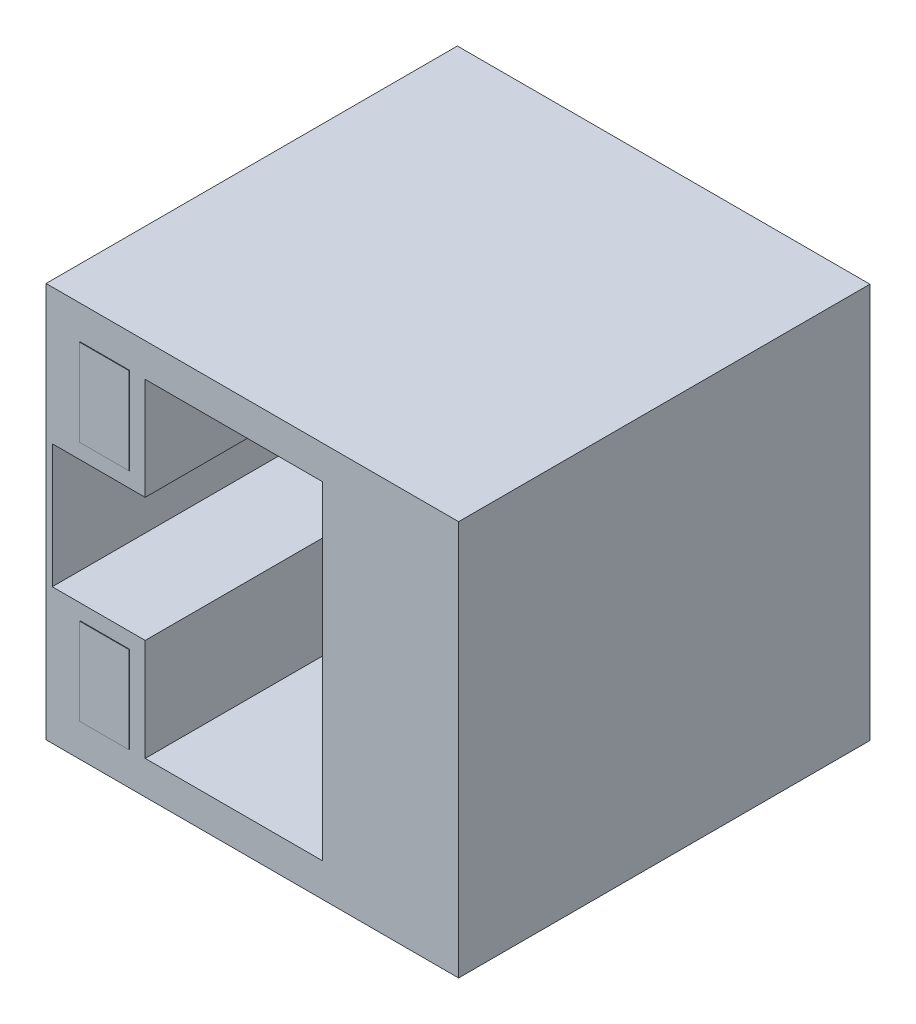
SolidWorks part; units mm, degrees
ref_plane "Front Plane" through (0, 0, 0) normal (0, 0, 1) x (1, 0, 0)
ref_plane "Top Plane" through (0, 0, 0) normal (0, 1, 0) x (1, 0, 0)
ref_plane "Right Plane" through (0, 0, 0) normal (1, 0, 0) x (0, 0, -1)
ref_plane "Plane1" through (0, 8.1026, 0) normal (0, 1, 0) x (-1, 0, 0)
sketch "Sketch1" plane through (0, 8.1026, 0) normal (0, 1, 0) x (-1, 0, 0)
  line L0 (-8.4582, -8.4328) -> (8.4582, -8.4328)
  line L1 (8.4582, -8.4328) -> (8.4582, 8.4328)
  line L2 (8.4582, 8.4328) -> (-8.4582, 8.4328)
  line L3 (-8.4582, 8.4328) -> (-8.4582, -8.4328)
extrude "Boss-Extrude1" add sketch "Sketch1" against normal blind 16.2052
ref_plane "Plane2" through (0, 0, 8.4582) normal (0, 0, 1) x (1, 0, 0)
sketch "Sketch2" plane through (0, 0, 8.4582) normal (0, 0, 1) x (1, 0, 0)
  line L0 (-7.0612, -3.175) -> (-7.0612, -6.731)
  line L1 (-7.0612, -6.731) -> (-5.0292, -6.731)
  line L2 (-5.0292, -6.731) -> (-5.0292, -3.175)
  line L3 (-5.0292, -3.175) -> (-7.0612, -3.175)
  line L4 (-7.0612, 6.731) -> (-7.0612, 3.175)
  line L5 (-7.0612, 3.175) -> (-5.0292, 3.175)
  line L6 (-5.0292, 3.175) -> (-5.0292, 6.731)
  line L7 (-5.0292, 6.731) -> (-7.0612, 6.731)
extrude "Boss-Extrude2" add sketch "Sketch2" against normal up to next
ref_plane "Plane3" through (0, 0, -1.7272) normal (0, 0, -1) x (-1, 0, 0)
sketch "Sketch3" plane through (0, 0, -1.7272) normal (0, 0, -1) x (-1, 0, 0)
  line L0 (8.2042, 2.54) -> (4.3942, 2.54)
  line L1 (4.3942, 2.54) -> (4.3942, 6.731)
  line L2 (4.3942, 6.731) -> (-2.8702, 6.731)
  line L3 (-2.8702, 6.731) -> (-2.8702, -6.731)
  line L4 (-2.8702, -6.731) -> (4.3942, -6.731)
  line L5 (4.3942, -6.731) -> (4.3942, -2.54)
  line L6 (4.3942, -2.54) -> (8.2042, -2.54)
  line L7 (8.2042, -2.54) -> (8.2042, 2.54)
extrude "Cut-Extrude1" cut sketch "Sketch3" against normal up to next
